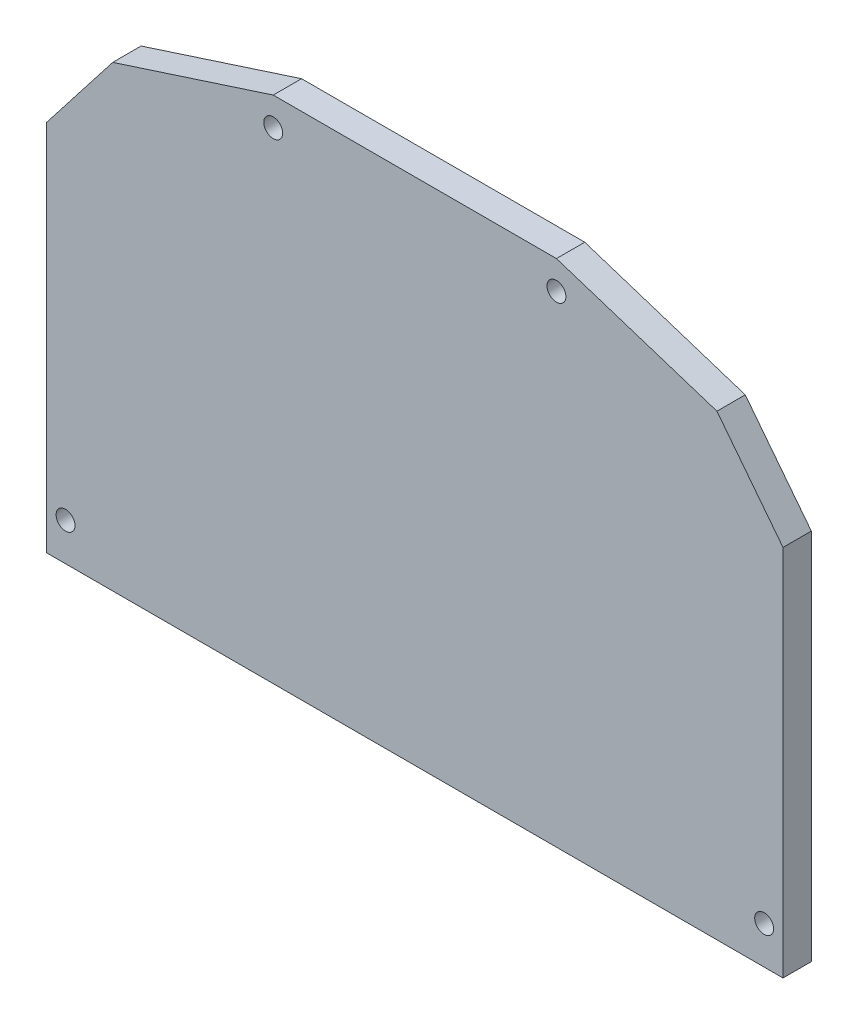
SolidWorks part; units mm, degrees
ref_plane "前视基准面" through (0, 0, 0) normal (0, 0, 1) x (1, 0, 0)
ref_plane "上视基准面" through (0, 0, 0) normal (0, 1, 0) x (1, 0, 0)
ref_plane "右视基准面" through (0, 0, 0) normal (1, 0, 0) x (0, 0, -1)
sketch "草图1" plane through (0, 0, 0) normal (0, 0, 1) x (1, 0, 0)
  line L3 (-8, 125.5) -> (-15, 134.5) construction
  line L4 (-8, 86) -> (-8, 125.5) construction
  line L5 (-15, 134.5) -> (-32, 140) construction
  line L6 (-32, 140) -> (-62, 140) construction
  line L7 (-62, 140) -> (-79, 134.5) construction
  line L8 (-79, 134.5) -> (-86, 125.5) construction
  line L9 (-86, 125.5) -> (-86, 86) construction
  line L10 (-86, 86) -> (-8, 86) construction
  line L11 (-8, 125.5) -> (-15, 134.5)
  line L12 (-8, 86) -> (-8, 125.5)
  line L13 (-15, 134.5) -> (-32, 140)
  line L14 (-32, 140) -> (-62, 140)
  line L15 (-62, 140) -> (-79, 134.5)
  line L16 (-79, 134.5) -> (-86, 125.5)
  line L17 (-86, 125.5) -> (-86, 86)
  line L18 (-86, 86) -> (-8, 86)
  circle A0 centre (-32, 137) radius 1 construction
  circle A1 centre (-62, 137) radius 1 construction
  circle A2 centre (-84, 90) radius 1 construction
  circle A3 centre (-10, 90) radius 1 construction
  circle A4 centre (-32, 137) radius 1
  circle A5 centre (-62, 137) radius 1
  circle A6 centre (-84, 90) radius 1
  circle A7 centre (-10, 90) radius 1
extrude "凸台-拉伸1" add sketch "草图1" along normal blind 3
